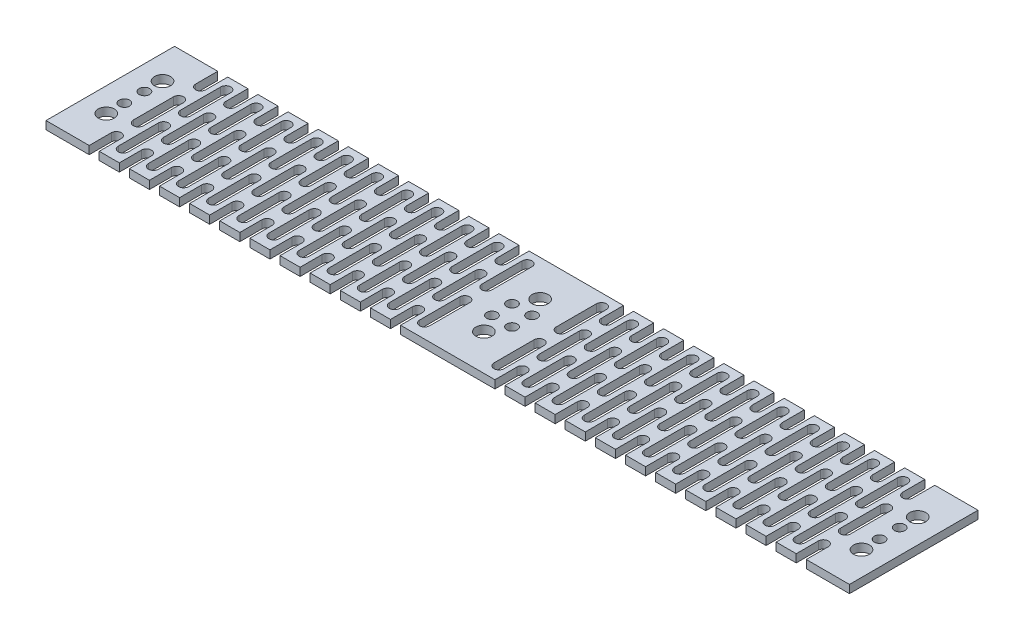
SolidWorks part; units mm, degrees
ref_plane "정면" through (0, 0, 0) normal (0, 0, 1) x (1, 0, 0)
ref_plane "윗면" through (0, 0, 0) normal (0, 1, 0) x (1, 0, 0)
ref_plane "우측면" through (0, 0, 0) normal (1, 0, 0) x (0, 0, -1)
sketch "스케치1" plane through (0, 0, 0) normal (0, 1, 0) x (1, 0, 0)
  line L1 (-50, 8) -> (50, 8)
  line L2 (-50, 8) -> (-50, -8)
  line L3 (-50, -8) -> (50, -8)
  line L4 (50, 8) -> (50, -8)
  dimension "D3" = 50
  dimension "D1" = 16
  dimension "D2" = 100
  dimension "D4" = 8
extrude "보스-돌출1" add sketch "스케치1" along normal blind 1 contours L1 L4 L3 L2
sketch "스케치2" plane through (0, 1, 0) normal (0, 1, 0) x (1, 0, 0)
  line L4 (50, 8) -> (50, -8) construction
  line L5 (-52.7608, 0) -> (58.8086, 0) construction
  line L6 (0, 14.085) -> (0, -13.5662) construction
  circle A2 centre (47, 3.5) radius 1
  circle A3 centre (0, 3.5) radius 1
  circle A4 centre (-47, 3.5) radius 1
  circle A8 centre (47, 1.25) radius 0.65
  circle A11 centre (-47, 1.25) radius 0.65
  circle A12 centre (47, -6.5) radius 1 [skipped]
  circle A13 centre (0, -6.5) radius 1 [skipped]
  circle A14 centre (-47, -6.5) radius 1 [skipped]
  circle A16 centre (1.25, 1.25) radius 0.65
  circle A17 centre (-1.25, 1.25) radius 0.65
  circle A18 centre (47, -1.25) radius 0.65
  circle A19 centre (47, -3.5) radius 1
  circle A20 centre (-1.25, -1.25) radius 0.65
  circle A21 centre (1.25, -1.25) radius 0.65
  circle A22 centre (0, -3.5) radius 1
  circle A23 centre (-47, -1.25) radius 0.65
  circle A24 centre (-47, -3.5) radius 1
  dimension "D4" = 2
  dimension "D9" = 1.3
  dimension "D11" = 2
  dimension "D5" = 3
  dimension "D6" = 3.5
  dimension "D10" = 1.25
  dimension "D12" = 2
  dimension "D7" = 3
  dimension "D8" = 2
extrude "컷-돌출1" cut sketch "스케치2" against normal through all
sketch "스케치3" plane through (0, 1, 0) normal (0, 1, 0) x (1, 0, 0)
  line L0 (44, 2.5) -> (44, -2.5) construction
  line L1 (44.625, 2.5) -> (44.625, -2.5)
  line L2 (43.375, 2.5) -> (43.375, -2.5)
  line L3 (-50, 8) -> (50, 8) construction
  line L4 (50, 8) -> (50, -8) construction
  line L5 (40.25, 2.5) -> (40.25, -2.5) construction
  line L6 (40.875, 2.5) -> (40.875, -2.5)
  line L7 (39.625, 2.5) -> (39.625, -2.5)
  line L8 (36.5, 2.5) -> (36.5, -2.5) construction
  line L9 (37.125, 2.5) -> (37.125, -2.5)
  line L10 (35.875, 2.5) -> (35.875, -2.5)
  line L11 (32.75, 2.5) -> (32.75, -2.5) construction
  line L12 (33.375, 2.5) -> (33.375, -2.5)
  line L13 (32.125, 2.5) -> (32.125, -2.5)
  line L14 (29, 2.5) -> (29, -2.5) construction
  line L15 (29.625, 2.5) -> (29.625, -2.5)
  line L16 (28.375, 2.5) -> (28.375, -2.5)
  line L17 (25.25, 2.5) -> (25.25, -2.5) construction
  line L18 (25.875, 2.5) -> (25.875, -2.5)
  line L19 (24.625, 2.5) -> (24.625, -2.5)
  line L20 (21.5, 2.5) -> (21.5, -2.5) construction
  line L21 (22.125, 2.5) -> (22.125, -2.5)
  line L22 (20.875, 2.5) -> (20.875, -2.5)
  line L23 (17.75, 2.5) -> (17.75, -2.5) construction
  line L24 (18.375, 2.5) -> (18.375, -2.5)
  line L25 (17.125, 2.5) -> (17.125, -2.5)
  line L26 (14, 2.5) -> (14, -2.5) construction
  line L27 (14.625, 2.5) -> (14.625, -2.5)
  line L28 (13.375, 2.5) -> (13.375, -2.5)
  line L29 (10.25, 2.5) -> (10.25, -2.5) construction
  line L30 (10.875, 2.5) -> (10.875, -2.5)
  line L31 (9.625, 2.5) -> (9.625, -2.5)
  line L32 (6.5, 2.5) -> (6.5, -2.5) construction
  line L33 (7.125, 2.5) -> (7.125, -2.5)
  line L34 (5.875, 2.5) -> (5.875, -2.5)
  line L35 (40.25, 10.25) -> (40.25, 5.25) construction
  line L36 (40.875, 10.25) -> (40.875, 5.25)
  line L37 (39.625, 10.25) -> (39.625, 5.25)
  line L38 (36.5, 10.25) -> (36.5, 5.25) construction
  line L39 (37.125, 10.25) -> (37.125, 5.25)
  line L40 (35.875, 10.25) -> (35.875, 5.25)
  line L41 (32.75, 10.25) -> (32.75, 5.25) construction
  line L42 (33.375, 10.25) -> (33.375, 5.25)
  line L43 (32.125, 10.25) -> (32.125, 5.25)
  line L44 (29, 10.25) -> (29, 5.25) construction
  line L45 (29.625, 10.25) -> (29.625, 5.25)
  line L46 (28.375, 10.25) -> (28.375, 5.25)
  line L47 (25.25, 10.25) -> (25.25, 5.25) construction
  line L48 (25.875, 10.25) -> (25.875, 5.25)
  line L49 (24.625, 10.25) -> (24.625, 5.25)
  line L50 (21.5, 10.25) -> (21.5, 5.25) construction
  line L51 (22.125, 10.25) -> (22.125, 5.25)
  line L52 (20.875, 10.25) -> (20.875, 5.25)
  line L53 (17.75, 10.25) -> (17.75, 5.25) construction
  line L54 (18.375, 10.25) -> (18.375, 5.25)
  line L55 (17.125, 10.25) -> (17.125, 5.25)
  line L56 (14, 10.25) -> (14, 5.25) construction
  line L57 (14.625, 10.25) -> (14.625, 5.25)
  line L58 (13.375, 10.25) -> (13.375, 5.25)
  line L59 (10.25, 10.25) -> (10.25, 5.25) construction
  line L60 (10.875, 10.25) -> (10.875, 5.25)
  line L61 (9.625, 10.25) -> (9.625, 5.25)
  line L62 (6.5, 10.25) -> (6.5, 5.25) construction
  line L63 (7.125, 10.25) -> (7.125, 5.25)
  line L64 (5.875, 10.25) -> (5.875, 5.25)
  line L65 (44, 10.25) -> (44, 5.25) construction
  line L66 (44.625, 10.25) -> (44.625, 5.25)
  line L67 (43.375, 10.25) -> (43.375, 5.25)
  line L68 (0, 0) -> (57.0875, 0) construction
  line L69 (-52.7608, 0) -> (58.8086, 0) construction
  line L70 (44, -10.25) -> (44, -5.25) construction
  line L71 (44.625, -10.25) -> (44.625, -5.25)
  line L72 (43.375, -10.25) -> (43.375, -5.25)
  line L73 (6.5, -10.25) -> (6.5, -5.25) construction
  line L74 (7.125, -10.25) -> (7.125, -5.25)
  line L75 (5.875, -10.25) -> (5.875, -5.25)
  line L76 (10.25, -10.25) -> (10.25, -5.25) construction
  line L77 (10.875, -10.25) -> (10.875, -5.25)
  line L78 (9.625, -10.25) -> (9.625, -5.25)
  line L79 (14, -10.25) -> (14, -5.25) construction
  line L80 (14.625, -10.25) -> (14.625, -5.25)
  line L81 (13.375, -10.25) -> (13.375, -5.25)
  line L82 (17.75, -10.25) -> (17.75, -5.25) construction
  line L83 (18.375, -10.25) -> (18.375, -5.25)
  line L84 (17.125, -10.25) -> (17.125, -5.25)
  line L85 (21.5, -10.25) -> (21.5, -5.25) construction
  line L86 (22.125, -10.25) -> (22.125, -5.25)
  line L87 (20.875, -10.25) -> (20.875, -5.25)
  line L88 (25.25, -10.25) -> (25.25, -5.25) construction
  line L89 (25.875, -10.25) -> (25.875, -5.25)
  line L90 (24.625, -10.25) -> (24.625, -5.25)
  line L91 (29, -10.25) -> (29, -5.25) construction
  line L92 (29.625, -10.25) -> (29.625, -5.25)
  line L93 (28.375, -10.25) -> (28.375, -5.25)
  line L94 (32.75, -10.25) -> (32.75, -5.25) construction
  line L95 (33.375, -10.25) -> (33.375, -5.25)
  line L96 (32.125, -10.25) -> (32.125, -5.25)
  line L97 (36.5, -10.25) -> (36.5, -5.25) construction
  line L98 (37.125, -10.25) -> (37.125, -5.25)
  line L99 (35.875, -10.25) -> (35.875, -5.25)
  line L100 (40.25, -10.25) -> (40.25, -5.25) construction
  line L101 (40.875, -10.25) -> (40.875, -5.25)
  line L102 (39.625, -10.25) -> (39.625, -5.25)
  line L103 (42.125, -1.25) -> (42.125, -6.25) construction
  line L104 (42.75, -1.25) -> (42.75, -6.25)
  line L105 (41.5, -1.25) -> (41.5, -6.25)
  line L106 (38.375, -1.25) -> (38.375, -6.25) construction
  line L107 (39, -1.25) -> (39, -6.25)
  line L108 (37.75, -1.25) -> (37.75, -6.25)
  line L109 (34.625, -1.25) -> (34.625, -6.25) construction
  line L110 (35.25, -1.25) -> (35.25, -6.25)
  line L111 (34, -1.25) -> (34, -6.25)
  line L112 (30.875, -1.25) -> (30.875, -6.25) construction
  line L113 (31.5, -1.25) -> (31.5, -6.25)
  line L114 (30.25, -1.25) -> (30.25, -6.25)
  line L115 (27.125, -1.25) -> (27.125, -6.25) construction
  line L116 (27.75, -1.25) -> (27.75, -6.25)
  line L117 (26.5, -1.25) -> (26.5, -6.25)
  line L118 (23.375, -1.25) -> (23.375, -6.25) construction
  line L119 (24, -1.25) -> (24, -6.25)
  line L120 (22.75, -1.25) -> (22.75, -6.25)
  line L121 (19.625, -1.25) -> (19.625, -6.25) construction
  line L122 (20.25, -1.25) -> (20.25, -6.25)
  line L123 (19, -1.25) -> (19, -6.25)
  line L124 (15.875, -1.25) -> (15.875, -6.25) construction
  line L125 (16.5, -1.25) -> (16.5, -6.25)
  line L126 (15.25, -1.25) -> (15.25, -6.25)
  line L127 (12.125, -1.25) -> (12.125, -6.25) construction
  line L128 (12.75, -1.25) -> (12.75, -6.25)
  line L129 (11.5, -1.25) -> (11.5, -6.25)
  line L130 (8.375, -1.25) -> (8.375, -6.25) construction
  line L131 (9, -1.25) -> (9, -6.25)
  line L132 (7.75, -1.25) -> (7.75, -6.25)
  line L133 (4.625, -1.25) -> (4.625, -6.25) construction
  line L134 (5.25, -1.25) -> (5.25, -6.25)
  line L135 (4, -1.25) -> (4, -6.25)
  line L136 (38.375, 6.5) -> (38.375, 1.5) construction
  line L137 (39, 6.5) -> (39, 1.5)
  line L138 (37.75, 6.5) -> (37.75, 1.5)
  line L139 (34.625, 6.5) -> (34.625, 1.5) construction
  line L140 (35.25, 6.5) -> (35.25, 1.5)
  line L141 (34, 6.5) -> (34, 1.5)
  line L142 (30.875, 6.5) -> (30.875, 1.5) construction
  line L143 (31.5, 6.5) -> (31.5, 1.5)
  line L144 (30.25, 6.5) -> (30.25, 1.5)
  line L145 (27.125, 6.5) -> (27.125, 1.5) construction
  line L146 (27.75, 6.5) -> (27.75, 1.5)
  line L147 (26.5, 6.5) -> (26.5, 1.5)
  line L148 (23.375, 6.5) -> (23.375, 1.5) construction
  line L149 (24, 6.5) -> (24, 1.5)
  line L150 (22.75, 6.5) -> (22.75, 1.5)
  line L151 (19.625, 6.5) -> (19.625, 1.5) construction
  line L152 (20.25, 6.5) -> (20.25, 1.5)
  line L153 (19, 6.5) -> (19, 1.5)
  line L154 (15.875, 6.5) -> (15.875, 1.5) construction
  line L155 (16.5, 6.5) -> (16.5, 1.5)
  line L156 (15.25, 6.5) -> (15.25, 1.5)
  line L157 (12.125, 6.5) -> (12.125, 1.5) construction
  line L158 (12.75, 6.5) -> (12.75, 1.5)
  line L159 (11.5, 6.5) -> (11.5, 1.5)
  line L160 (8.375, 6.5) -> (8.375, 1.5) construction
  line L161 (9, 6.5) -> (9, 1.5)
  line L162 (7.75, 6.5) -> (7.75, 1.5)
  line L163 (4.625, 6.5) -> (4.625, 1.5) construction
  line L164 (5.25, 6.5) -> (5.25, 1.5)
  line L165 (4, 6.5) -> (4, 1.5)
  line L166 (42.125, 6.5) -> (42.125, 1.5) construction
  line L167 (42.75, 6.5) -> (42.75, 1.5)
  line L168 (41.5, 6.5) -> (41.5, 1.5)
  line L169 (0, 14.085) -> (0, -13.5662) construction
  line L170 (-42.125, 6.5) -> (-42.125, 1.5) construction
  line L171 (-42.75, 6.5) -> (-42.75, 1.5)
  line L172 (-41.5, 6.5) -> (-41.5, 1.5)
  line L173 (-4.625, 6.5) -> (-4.625, 1.5) construction
  line L174 (-5.25, 6.5) -> (-5.25, 1.5)
  line L175 (-4, 6.5) -> (-4, 1.5)
  line L176 (-8.375, 6.5) -> (-8.375, 1.5) construction
  line L177 (-9, 6.5) -> (-9, 1.5)
  line L178 (-7.75, 6.5) -> (-7.75, 1.5)
  line L179 (-12.125, 6.5) -> (-12.125, 1.5) construction
  line L180 (-12.75, 6.5) -> (-12.75, 1.5)
  line L181 (-11.5, 6.5) -> (-11.5, 1.5)
  line L182 (-15.875, 6.5) -> (-15.875, 1.5) construction
  line L183 (-16.5, 6.5) -> (-16.5, 1.5)
  line L184 (-15.25, 6.5) -> (-15.25, 1.5)
  line L185 (-19.625, 6.5) -> (-19.625, 1.5) construction
  line L186 (-20.25, 6.5) -> (-20.25, 1.5)
  line L187 (-19, 6.5) -> (-19, 1.5)
  line L188 (-23.375, 6.5) -> (-23.375, 1.5) construction
  line L189 (-24, 6.5) -> (-24, 1.5)
  line L190 (-22.75, 6.5) -> (-22.75, 1.5)
  line L191 (-27.125, 6.5) -> (-27.125, 1.5) construction
  line L192 (-27.75, 6.5) -> (-27.75, 1.5)
  line L193 (-26.5, 6.5) -> (-26.5, 1.5)
  line L194 (-30.875, 6.5) -> (-30.875, 1.5) construction
  line L195 (-31.5, 6.5) -> (-31.5, 1.5)
  line L196 (-30.25, 6.5) -> (-30.25, 1.5)
  line L197 (-34.625, 6.5) -> (-34.625, 1.5) construction
  line L198 (-35.25, 6.5) -> (-35.25, 1.5)
  line L199 (-34, 6.5) -> (-34, 1.5)
  line L200 (-38.375, 6.5) -> (-38.375, 1.5) construction
  line L201 (-39, 6.5) -> (-39, 1.5)
  line L202 (-37.75, 6.5) -> (-37.75, 1.5)
  line L203 (-4.625, -1.25) -> (-4.625, -6.25) construction
  line L204 (-5.25, -1.25) -> (-5.25, -6.25)
  line L205 (-4, -1.25) -> (-4, -6.25)
  line L206 (-8.375, -1.25) -> (-8.375, -6.25) construction
  line L207 (-9, -1.25) -> (-9, -6.25)
  line L208 (-7.75, -1.25) -> (-7.75, -6.25)
  line L209 (-12.125, -1.25) -> (-12.125, -6.25) construction
  line L210 (-12.75, -1.25) -> (-12.75, -6.25)
  line L211 (-11.5, -1.25) -> (-11.5, -6.25)
  line L212 (-15.875, -1.25) -> (-15.875, -6.25) construction
  line L213 (-16.5, -1.25) -> (-16.5, -6.25)
  line L214 (-15.25, -1.25) -> (-15.25, -6.25)
  line L215 (-19.625, -1.25) -> (-19.625, -6.25) construction
  line L216 (-20.25, -1.25) -> (-20.25, -6.25)
  line L217 (-19, -1.25) -> (-19, -6.25)
  line L218 (-23.375, -1.25) -> (-23.375, -6.25) construction
  line L219 (-24, -1.25) -> (-24, -6.25)
  line L220 (-22.75, -1.25) -> (-22.75, -6.25)
  line L221 (-27.125, -1.25) -> (-27.125, -6.25) construction
  line L222 (-27.75, -1.25) -> (-27.75, -6.25)
  line L223 (-26.5, -1.25) -> (-26.5, -6.25)
  line L224 (-30.875, -1.25) -> (-30.875, -6.25) construction
  line L225 (-31.5, -1.25) -> (-31.5, -6.25)
  line L226 (-30.25, -1.25) -> (-30.25, -6.25)
  line L227 (-34.625, -1.25) -> (-34.625, -6.25) construction
  line L228 (-35.25, -1.25) -> (-35.25, -6.25)
  line L229 (-34, -1.25) -> (-34, -6.25)
  line L230 (-38.375, -1.25) -> (-38.375, -6.25) construction
  line L231 (-39, -1.25) -> (-39, -6.25)
  line L232 (-37.75, -1.25) -> (-37.75, -6.25)
  line L233 (-42.125, -1.25) -> (-42.125, -6.25) construction
  line L234 (-42.75, -1.25) -> (-42.75, -6.25)
  line L235 (-41.5, -1.25) -> (-41.5, -6.25)
  line L236 (-40.25, -10.25) -> (-40.25, -5.25) construction
  line L237 (-40.875, -10.25) -> (-40.875, -5.25)
  line L238 (-39.625, -10.25) -> (-39.625, -5.25)
  line L239 (-36.5, -10.25) -> (-36.5, -5.25) construction
  line L240 (-37.125, -10.25) -> (-37.125, -5.25)
  line L241 (-35.875, -10.25) -> (-35.875, -5.25)
  line L242 (-32.75, -10.25) -> (-32.75, -5.25) construction
  line L243 (-33.375, -10.25) -> (-33.375, -5.25)
  line L244 (-32.125, -10.25) -> (-32.125, -5.25)
  line L245 (-29, -10.25) -> (-29, -5.25) construction
  line L246 (-29.625, -10.25) -> (-29.625, -5.25)
  line L247 (-28.375, -10.25) -> (-28.375, -5.25)
  line L248 (-25.25, -10.25) -> (-25.25, -5.25) construction
  line L249 (-25.875, -10.25) -> (-25.875, -5.25)
  line L250 (-24.625, -10.25) -> (-24.625, -5.25)
  line L251 (-21.5, -10.25) -> (-21.5, -5.25) construction
  line L252 (-22.125, -10.25) -> (-22.125, -5.25)
  line L253 (-20.875, -10.25) -> (-20.875, -5.25)
  line L254 (-17.75, -10.25) -> (-17.75, -5.25) construction
  line L255 (-18.375, -10.25) -> (-18.375, -5.25)
  line L256 (-17.125, -10.25) -> (-17.125, -5.25)
  line L257 (-14, -10.25) -> (-14, -5.25) construction
  line L258 (-14.625, -10.25) -> (-14.625, -5.25)
  line L259 (-13.375, -10.25) -> (-13.375, -5.25)
  line L260 (-10.25, -10.25) -> (-10.25, -5.25) construction
  line L261 (-10.875, -10.25) -> (-10.875, -5.25)
  line L262 (-9.625, -10.25) -> (-9.625, -5.25)
  line L263 (-6.5, -10.25) -> (-6.5, -5.25) construction
  line L264 (-7.125, -10.25) -> (-7.125, -5.25)
  line L265 (-5.875, -10.25) -> (-5.875, -5.25)
  line L266 (-44, -10.25) -> (-44, -5.25) construction
  line L267 (-44.625, -10.25) -> (-44.625, -5.25)
  line L268 (-43.375, -10.25) -> (-43.375, -5.25)
  line L269 (-44, 10.25) -> (-44, 5.25) construction
  line L270 (-44.625, 10.25) -> (-44.625, 5.25)
  line L271 (-43.375, 10.25) -> (-43.375, 5.25)
  line L272 (-6.5, 10.25) -> (-6.5, 5.25) construction
  line L273 (-7.125, 10.25) -> (-7.125, 5.25)
  line L274 (-5.875, 10.25) -> (-5.875, 5.25)
  line L275 (-10.25, 10.25) -> (-10.25, 5.25) construction
  line L276 (-10.875, 10.25) -> (-10.875, 5.25)
  line L277 (-9.625, 10.25) -> (-9.625, 5.25)
  line L278 (-14, 10.25) -> (-14, 5.25) construction
  line L279 (-14.625, 10.25) -> (-14.625, 5.25)
  line L280 (-13.375, 10.25) -> (-13.375, 5.25)
  line L281 (-17.75, 10.25) -> (-17.75, 5.25) construction
  line L282 (-18.375, 10.25) -> (-18.375, 5.25)
  line L283 (-17.125, 10.25) -> (-17.125, 5.25)
  line L284 (-21.5, 10.25) -> (-21.5, 5.25) construction
  line L285 (-22.125, 10.25) -> (-22.125, 5.25)
  line L286 (-20.875, 10.25) -> (-20.875, 5.25)
  line L287 (-25.25, 10.25) -> (-25.25, 5.25) construction
  line L288 (-25.875, 10.25) -> (-25.875, 5.25)
  line L289 (-24.625, 10.25) -> (-24.625, 5.25)
  line L290 (-29, 10.25) -> (-29, 5.25) construction
  line L291 (-29.625, 10.25) -> (-29.625, 5.25)
  line L292 (-28.375, 10.25) -> (-28.375, 5.25)
  line L293 (-32.75, 10.25) -> (-32.75, 5.25) construction
  line L294 (-33.375, 10.25) -> (-33.375, 5.25)
  line L295 (-32.125, 10.25) -> (-32.125, 5.25)
  line L296 (-36.5, 10.25) -> (-36.5, 5.25) construction
  line L297 (-37.125, 10.25) -> (-37.125, 5.25)
  line L298 (-35.875, 10.25) -> (-35.875, 5.25)
  line L299 (-40.25, 10.25) -> (-40.25, 5.25) construction
  line L300 (-40.875, 10.25) -> (-40.875, 5.25)
  line L301 (-39.625, 10.25) -> (-39.625, 5.25)
  line L302 (-6.5, 2.5) -> (-6.5, -2.5) construction
  line L303 (-7.125, 2.5) -> (-7.125, -2.5)
  line L304 (-5.875, 2.5) -> (-5.875, -2.5)
  line L305 (-10.25, 2.5) -> (-10.25, -2.5) construction
  line L306 (-10.875, 2.5) -> (-10.875, -2.5)
  line L307 (-9.625, 2.5) -> (-9.625, -2.5)
  line L308 (-14, 2.5) -> (-14, -2.5) construction
  line L309 (-14.625, 2.5) -> (-14.625, -2.5)
  line L310 (-13.375, 2.5) -> (-13.375, -2.5)
  line L311 (-17.75, 2.5) -> (-17.75, -2.5) construction
  line L312 (-18.375, 2.5) -> (-18.375, -2.5)
  line L313 (-17.125, 2.5) -> (-17.125, -2.5)
  line L314 (-21.5, 2.5) -> (-21.5, -2.5) construction
  line L315 (-22.125, 2.5) -> (-22.125, -2.5)
  line L316 (-20.875, 2.5) -> (-20.875, -2.5)
  line L317 (-25.25, 2.5) -> (-25.25, -2.5) construction
  line L318 (-25.875, 2.5) -> (-25.875, -2.5)
  line L319 (-24.625, 2.5) -> (-24.625, -2.5)
  line L320 (-29, 2.5) -> (-29, -2.5) construction
  line L321 (-29.625, 2.5) -> (-29.625, -2.5)
  line L322 (-28.375, 2.5) -> (-28.375, -2.5)
  line L323 (-32.75, 2.5) -> (-32.75, -2.5) construction
  line L324 (-33.375, 2.5) -> (-33.375, -2.5)
  line L325 (-32.125, 2.5) -> (-32.125, -2.5)
  line L326 (-36.5, 2.5) -> (-36.5, -2.5) construction
  line L327 (-37.125, 2.5) -> (-37.125, -2.5)
  line L328 (-35.875, 2.5) -> (-35.875, -2.5)
  line L329 (-40.25, 2.5) -> (-40.25, -2.5) construction
  line L330 (-40.875, 2.5) -> (-40.875, -2.5)
  line L331 (-39.625, 2.5) -> (-39.625, -2.5)
  line L332 (-44, 2.5) -> (-44, -2.5) construction
  line L333 (-44.625, 2.5) -> (-44.625, -2.5)
  line L334 (-43.375, 2.5) -> (-43.375, -2.5)
  arc A0 (44.625, 2.5) -> (43.375, 2.5) centre (44, 2.5) ccw
  arc A1 (43.375, -2.5) -> (44.625, -2.5) centre (44, -2.5) ccw
  arc A2 (40.875, 2.5) -> (39.625, 2.5) centre (40.25, 2.5) ccw
  arc A3 (39.625, -2.5) -> (40.875, -2.5) centre (40.25, -2.5) ccw
  arc A4 (37.125, 2.5) -> (35.875, 2.5) centre (36.5, 2.5) ccw
  arc A5 (35.875, -2.5) -> (37.125, -2.5) centre (36.5, -2.5) ccw
  arc A6 (33.375, 2.5) -> (32.125, 2.5) centre (32.75, 2.5) ccw
  arc A7 (32.125, -2.5) -> (33.375, -2.5) centre (32.75, -2.5) ccw
  arc A8 (29.625, 2.5) -> (28.375, 2.5) centre (29, 2.5) ccw
  arc A9 (28.375, -2.5) -> (29.625, -2.5) centre (29, -2.5) ccw
  arc A10 (25.875, 2.5) -> (24.625, 2.5) centre (25.25, 2.5) ccw
  arc A11 (24.625, -2.5) -> (25.875, -2.5) centre (25.25, -2.5) ccw
  arc A12 (22.125, 2.5) -> (20.875, 2.5) centre (21.5, 2.5) ccw
  arc A13 (20.875, -2.5) -> (22.125, -2.5) centre (21.5, -2.5) ccw
  arc A14 (18.375, 2.5) -> (17.125, 2.5) centre (17.75, 2.5) ccw
  arc A15 (17.125, -2.5) -> (18.375, -2.5) centre (17.75, -2.5) ccw
  arc A16 (14.625, 2.5) -> (13.375, 2.5) centre (14, 2.5) ccw
  arc A17 (13.375, -2.5) -> (14.625, -2.5) centre (14, -2.5) ccw
  arc A18 (10.875, 2.5) -> (9.625, 2.5) centre (10.25, 2.5) ccw
  arc A19 (9.625, -2.5) -> (10.875, -2.5) centre (10.25, -2.5) ccw
  arc A20 (7.125, 2.5) -> (5.875, 2.5) centre (6.5, 2.5) ccw
  arc A21 (5.875, -2.5) -> (7.125, -2.5) centre (6.5, -2.5) ccw
  arc A22 (40.875, 10.25) -> (39.625, 10.25) centre (40.25, 10.25) ccw
  arc A23 (39.625, 5.25) -> (40.875, 5.25) centre (40.25, 5.25) ccw
  arc A24 (37.125, 10.25) -> (35.875, 10.25) centre (36.5, 10.25) ccw
  arc A25 (35.875, 5.25) -> (37.125, 5.25) centre (36.5, 5.25) ccw
  arc A26 (33.375, 10.25) -> (32.125, 10.25) centre (32.75, 10.25) ccw
  arc A27 (32.125, 5.25) -> (33.375, 5.25) centre (32.75, 5.25) ccw
  arc A28 (29.625, 10.25) -> (28.375, 10.25) centre (29, 10.25) ccw
  arc A29 (28.375, 5.25) -> (29.625, 5.25) centre (29, 5.25) ccw
  arc A30 (25.875, 10.25) -> (24.625, 10.25) centre (25.25, 10.25) ccw
  arc A31 (24.625, 5.25) -> (25.875, 5.25) centre (25.25, 5.25) ccw
  arc A32 (22.125, 10.25) -> (20.875, 10.25) centre (21.5, 10.25) ccw
  arc A33 (20.875, 5.25) -> (22.125, 5.25) centre (21.5, 5.25) ccw
  arc A34 (18.375, 10.25) -> (17.125, 10.25) centre (17.75, 10.25) ccw
  arc A35 (17.125, 5.25) -> (18.375, 5.25) centre (17.75, 5.25) ccw
  arc A36 (14.625, 10.25) -> (13.375, 10.25) centre (14, 10.25) ccw
  arc A37 (13.375, 5.25) -> (14.625, 5.25) centre (14, 5.25) ccw
  arc A38 (10.875, 10.25) -> (9.625, 10.25) centre (10.25, 10.25) ccw
  arc A39 (9.625, 5.25) -> (10.875, 5.25) centre (10.25, 5.25) ccw
  arc A40 (7.125, 10.25) -> (5.875, 10.25) centre (6.5, 10.25) ccw
  arc A41 (5.875, 5.25) -> (7.125, 5.25) centre (6.5, 5.25) ccw
  arc A42 (44.625, 10.25) -> (43.375, 10.25) centre (44, 10.25) ccw
  arc A43 (43.375, 5.25) -> (44.625, 5.25) centre (44, 5.25) ccw
  arc A44 (44.625, -10.25) -> (43.375, -10.25) centre (44, -10.25) cw
  arc A45 (43.375, -5.25) -> (44.625, -5.25) centre (44, -5.25) cw
  arc A46 (7.125, -10.25) -> (5.875, -10.25) centre (6.5, -10.25) cw
  arc A47 (5.875, -5.25) -> (7.125, -5.25) centre (6.5, -5.25) cw
  arc A48 (10.875, -10.25) -> (9.625, -10.25) centre (10.25, -10.25) cw
  arc A49 (9.625, -5.25) -> (10.875, -5.25) centre (10.25, -5.25) cw
  arc A50 (14.625, -10.25) -> (13.375, -10.25) centre (14, -10.25) cw
  arc A51 (13.375, -5.25) -> (14.625, -5.25) centre (14, -5.25) cw
  arc A52 (18.375, -10.25) -> (17.125, -10.25) centre (17.75, -10.25) cw
  arc A53 (17.125, -5.25) -> (18.375, -5.25) centre (17.75, -5.25) cw
  arc A54 (22.125, -10.25) -> (20.875, -10.25) centre (21.5, -10.25) cw
  arc A55 (20.875, -5.25) -> (22.125, -5.25) centre (21.5, -5.25) cw
  arc A56 (25.875, -10.25) -> (24.625, -10.25) centre (25.25, -10.25) cw
  arc A57 (24.625, -5.25) -> (25.875, -5.25) centre (25.25, -5.25) cw
  arc A58 (29.625, -10.25) -> (28.375, -10.25) centre (29, -10.25) cw
  arc A59 (28.375, -5.25) -> (29.625, -5.25) centre (29, -5.25) cw
  arc A60 (33.375, -10.25) -> (32.125, -10.25) centre (32.75, -10.25) cw
  arc A61 (32.125, -5.25) -> (33.375, -5.25) centre (32.75, -5.25) cw
  arc A62 (37.125, -10.25) -> (35.875, -10.25) centre (36.5, -10.25) cw
  arc A63 (35.875, -5.25) -> (37.125, -5.25) centre (36.5, -5.25) cw
  arc A64 (40.875, -10.25) -> (39.625, -10.25) centre (40.25, -10.25) cw
  arc A65 (39.625, -5.25) -> (40.875, -5.25) centre (40.25, -5.25) cw
  arc A66 (42.75, -1.25) -> (41.5, -1.25) centre (42.125, -1.25) ccw
  arc A67 (41.5, -6.25) -> (42.75, -6.25) centre (42.125, -6.25) ccw
  arc A68 (39, -1.25) -> (37.75, -1.25) centre (38.375, -1.25) ccw
  arc A69 (37.75, -6.25) -> (39, -6.25) centre (38.375, -6.25) ccw
  arc A70 (35.25, -1.25) -> (34, -1.25) centre (34.625, -1.25) ccw
  arc A71 (34, -6.25) -> (35.25, -6.25) centre (34.625, -6.25) ccw
  arc A72 (31.5, -1.25) -> (30.25, -1.25) centre (30.875, -1.25) ccw
  arc A73 (30.25, -6.25) -> (31.5, -6.25) centre (30.875, -6.25) ccw
  arc A74 (27.75, -1.25) -> (26.5, -1.25) centre (27.125, -1.25) ccw
  arc A75 (26.5, -6.25) -> (27.75, -6.25) centre (27.125, -6.25) ccw
  arc A76 (24, -1.25) -> (22.75, -1.25) centre (23.375, -1.25) ccw
  arc A77 (22.75, -6.25) -> (24, -6.25) centre (23.375, -6.25) ccw
  arc A78 (20.25, -1.25) -> (19, -1.25) centre (19.625, -1.25) ccw
  arc A79 (19, -6.25) -> (20.25, -6.25) centre (19.625, -6.25) ccw
  arc A80 (16.5, -1.25) -> (15.25, -1.25) centre (15.875, -1.25) ccw
  arc A81 (15.25, -6.25) -> (16.5, -6.25) centre (15.875, -6.25) ccw
  arc A82 (12.75, -1.25) -> (11.5, -1.25) centre (12.125, -1.25) ccw
  arc A83 (11.5, -6.25) -> (12.75, -6.25) centre (12.125, -6.25) ccw
  arc A84 (9, -1.25) -> (7.75, -1.25) centre (8.375, -1.25) ccw
  arc A85 (7.75, -6.25) -> (9, -6.25) centre (8.375, -6.25) ccw
  arc A86 (5.25, -1.25) -> (4, -1.25) centre (4.625, -1.25) ccw
  arc A87 (4, -6.25) -> (5.25, -6.25) centre (4.625, -6.25) ccw
  arc A88 (39, 6.5) -> (37.75, 6.5) centre (38.375, 6.5) ccw
  arc A89 (37.75, 1.5) -> (39, 1.5) centre (38.375, 1.5) ccw
  arc A90 (35.25, 6.5) -> (34, 6.5) centre (34.625, 6.5) ccw
  arc A91 (34, 1.5) -> (35.25, 1.5) centre (34.625, 1.5) ccw
  arc A92 (31.5, 6.5) -> (30.25, 6.5) centre (30.875, 6.5) ccw
  arc A93 (30.25, 1.5) -> (31.5, 1.5) centre (30.875, 1.5) ccw
  arc A94 (27.75, 6.5) -> (26.5, 6.5) centre (27.125, 6.5) ccw
  arc A95 (26.5, 1.5) -> (27.75, 1.5) centre (27.125, 1.5) ccw
  arc A96 (24, 6.5) -> (22.75, 6.5) centre (23.375, 6.5) ccw
  arc A97 (22.75, 1.5) -> (24, 1.5) centre (23.375, 1.5) ccw
  arc A98 (20.25, 6.5) -> (19, 6.5) centre (19.625, 6.5) ccw
  arc A99 (19, 1.5) -> (20.25, 1.5) centre (19.625, 1.5) ccw
  arc A100 (16.5, 6.5) -> (15.25, 6.5) centre (15.875, 6.5) ccw
  arc A101 (15.25, 1.5) -> (16.5, 1.5) centre (15.875, 1.5) ccw
  arc A102 (12.75, 6.5) -> (11.5, 6.5) centre (12.125, 6.5) ccw
  arc A103 (11.5, 1.5) -> (12.75, 1.5) centre (12.125, 1.5) ccw
  arc A104 (9, 6.5) -> (7.75, 6.5) centre (8.375, 6.5) ccw
  arc A105 (7.75, 1.5) -> (9, 1.5) centre (8.375, 1.5) ccw
  arc A106 (5.25, 6.5) -> (4, 6.5) centre (4.625, 6.5) ccw
  arc A107 (4, 1.5) -> (5.25, 1.5) centre (4.625, 1.5) ccw
  arc A108 (42.75, 6.5) -> (41.5, 6.5) centre (42.125, 6.5) ccw
  arc A109 (41.5, 1.5) -> (42.75, 1.5) centre (42.125, 1.5) ccw
  arc A110 (-42.75, 6.5) -> (-41.5, 6.5) centre (-42.125, 6.5) cw
  arc A111 (-41.5, 1.5) -> (-42.75, 1.5) centre (-42.125, 1.5) cw
  arc A112 (-5.25, 6.5) -> (-4, 6.5) centre (-4.625, 6.5) cw
  arc A113 (-4, 1.5) -> (-5.25, 1.5) centre (-4.625, 1.5) cw
  arc A114 (-9, 6.5) -> (-7.75, 6.5) centre (-8.375, 6.5) cw
  arc A115 (-7.75, 1.5) -> (-9, 1.5) centre (-8.375, 1.5) cw
  arc A116 (-12.75, 6.5) -> (-11.5, 6.5) centre (-12.125, 6.5) cw
  arc A117 (-11.5, 1.5) -> (-12.75, 1.5) centre (-12.125, 1.5) cw
  arc A118 (-16.5, 6.5) -> (-15.25, 6.5) centre (-15.875, 6.5) cw
  arc A119 (-15.25, 1.5) -> (-16.5, 1.5) centre (-15.875, 1.5) cw
  arc A120 (-20.25, 6.5) -> (-19, 6.5) centre (-19.625, 6.5) cw
  arc A121 (-19, 1.5) -> (-20.25, 1.5) centre (-19.625, 1.5) cw
  arc A122 (-24, 6.5) -> (-22.75, 6.5) centre (-23.375, 6.5) cw
  arc A123 (-22.75, 1.5) -> (-24, 1.5) centre (-23.375, 1.5) cw
  arc A124 (-27.75, 6.5) -> (-26.5, 6.5) centre (-27.125, 6.5) cw
  arc A125 (-26.5, 1.5) -> (-27.75, 1.5) centre (-27.125, 1.5) cw
  arc A126 (-31.5, 6.5) -> (-30.25, 6.5) centre (-30.875, 6.5) cw
  arc A127 (-30.25, 1.5) -> (-31.5, 1.5) centre (-30.875, 1.5) cw
  arc A128 (-35.25, 6.5) -> (-34, 6.5) centre (-34.625, 6.5) cw
  arc A129 (-34, 1.5) -> (-35.25, 1.5) centre (-34.625, 1.5) cw
  arc A130 (-39, 6.5) -> (-37.75, 6.5) centre (-38.375, 6.5) cw
  arc A131 (-37.75, 1.5) -> (-39, 1.5) centre (-38.375, 1.5) cw
  arc A132 (-5.25, -1.25) -> (-4, -1.25) centre (-4.625, -1.25) cw
  arc A133 (-4, -6.25) -> (-5.25, -6.25) centre (-4.625, -6.25) cw
  arc A134 (-9, -1.25) -> (-7.75, -1.25) centre (-8.375, -1.25) cw
  arc A135 (-7.75, -6.25) -> (-9, -6.25) centre (-8.375, -6.25) cw
  arc A136 (-12.75, -1.25) -> (-11.5, -1.25) centre (-12.125, -1.25) cw
  arc A137 (-11.5, -6.25) -> (-12.75, -6.25) centre (-12.125, -6.25) cw
  arc A138 (-16.5, -1.25) -> (-15.25, -1.25) centre (-15.875, -1.25) cw
  arc A139 (-15.25, -6.25) -> (-16.5, -6.25) centre (-15.875, -6.25) cw
  arc A140 (-20.25, -1.25) -> (-19, -1.25) centre (-19.625, -1.25) cw
  arc A141 (-19, -6.25) -> (-20.25, -6.25) centre (-19.625, -6.25) cw
  arc A142 (-24, -1.25) -> (-22.75, -1.25) centre (-23.375, -1.25) cw
  arc A143 (-22.75, -6.25) -> (-24, -6.25) centre (-23.375, -6.25) cw
  arc A144 (-27.75, -1.25) -> (-26.5, -1.25) centre (-27.125, -1.25) cw
  arc A145 (-26.5, -6.25) -> (-27.75, -6.25) centre (-27.125, -6.25) cw
  arc A146 (-31.5, -1.25) -> (-30.25, -1.25) centre (-30.875, -1.25) cw
  arc A147 (-30.25, -6.25) -> (-31.5, -6.25) centre (-30.875, -6.25) cw
  arc A148 (-35.25, -1.25) -> (-34, -1.25) centre (-34.625, -1.25) cw
  arc A149 (-34, -6.25) -> (-35.25, -6.25) centre (-34.625, -6.25) cw
  arc A150 (-39, -1.25) -> (-37.75, -1.25) centre (-38.375, -1.25) cw
  arc A151 (-37.75, -6.25) -> (-39, -6.25) centre (-38.375, -6.25) cw
  arc A152 (-42.75, -1.25) -> (-41.5, -1.25) centre (-42.125, -1.25) cw
  arc A153 (-41.5, -6.25) -> (-42.75, -6.25) centre (-42.125, -6.25) cw
  arc A154 (-40.875, -10.25) -> (-39.625, -10.25) centre (-40.25, -10.25) ccw
  arc A155 (-39.625, -5.25) -> (-40.875, -5.25) centre (-40.25, -5.25) ccw
  arc A156 (-37.125, -10.25) -> (-35.875, -10.25) centre (-36.5, -10.25) ccw
  arc A157 (-35.875, -5.25) -> (-37.125, -5.25) centre (-36.5, -5.25) ccw
  arc A158 (-33.375, -10.25) -> (-32.125, -10.25) centre (-32.75, -10.25) ccw
  arc A159 (-32.125, -5.25) -> (-33.375, -5.25) centre (-32.75, -5.25) ccw
  arc A160 (-29.625, -10.25) -> (-28.375, -10.25) centre (-29, -10.25) ccw
  arc A161 (-28.375, -5.25) -> (-29.625, -5.25) centre (-29, -5.25) ccw
  arc A162 (-25.875, -10.25) -> (-24.625, -10.25) centre (-25.25, -10.25) ccw
  arc A163 (-24.625, -5.25) -> (-25.875, -5.25) centre (-25.25, -5.25) ccw
  arc A164 (-22.125, -10.25) -> (-20.875, -10.25) centre (-21.5, -10.25) ccw
  arc A165 (-20.875, -5.25) -> (-22.125, -5.25) centre (-21.5, -5.25) ccw
  arc A166 (-18.375, -10.25) -> (-17.125, -10.25) centre (-17.75, -10.25) ccw
  arc A167 (-17.125, -5.25) -> (-18.375, -5.25) centre (-17.75, -5.25) ccw
  arc A168 (-14.625, -10.25) -> (-13.375, -10.25) centre (-14, -10.25) ccw
  arc A169 (-13.375, -5.25) -> (-14.625, -5.25) centre (-14, -5.25) ccw
  arc A170 (-10.875, -10.25) -> (-9.625, -10.25) centre (-10.25, -10.25) ccw
  arc A171 (-9.625, -5.25) -> (-10.875, -5.25) centre (-10.25, -5.25) ccw
  arc A172 (-7.125, -10.25) -> (-5.875, -10.25) centre (-6.5, -10.25) ccw
  arc A173 (-5.875, -5.25) -> (-7.125, -5.25) centre (-6.5, -5.25) ccw
  arc A174 (-44.625, -10.25) -> (-43.375, -10.25) centre (-44, -10.25) ccw
  arc A175 (-43.375, -5.25) -> (-44.625, -5.25) centre (-44, -5.25) ccw
  arc A176 (-44.625, 10.25) -> (-43.375, 10.25) centre (-44, 10.25) cw
  arc A177 (-43.375, 5.25) -> (-44.625, 5.25) centre (-44, 5.25) cw
  arc A178 (-7.125, 10.25) -> (-5.875, 10.25) centre (-6.5, 10.25) cw
  arc A179 (-5.875, 5.25) -> (-7.125, 5.25) centre (-6.5, 5.25) cw
  arc A180 (-10.875, 10.25) -> (-9.625, 10.25) centre (-10.25, 10.25) cw
  arc A181 (-9.625, 5.25) -> (-10.875, 5.25) centre (-10.25, 5.25) cw
  arc A182 (-14.625, 10.25) -> (-13.375, 10.25) centre (-14, 10.25) cw
  arc A183 (-13.375, 5.25) -> (-14.625, 5.25) centre (-14, 5.25) cw
  arc A184 (-18.375, 10.25) -> (-17.125, 10.25) centre (-17.75, 10.25) cw
  arc A185 (-17.125, 5.25) -> (-18.375, 5.25) centre (-17.75, 5.25) cw
  arc A186 (-22.125, 10.25) -> (-20.875, 10.25) centre (-21.5, 10.25) cw
  arc A187 (-20.875, 5.25) -> (-22.125, 5.25) centre (-21.5, 5.25) cw
  arc A188 (-25.875, 10.25) -> (-24.625, 10.25) centre (-25.25, 10.25) cw
  arc A189 (-24.625, 5.25) -> (-25.875, 5.25) centre (-25.25, 5.25) cw
  arc A190 (-29.625, 10.25) -> (-28.375, 10.25) centre (-29, 10.25) cw
  arc A191 (-28.375, 5.25) -> (-29.625, 5.25) centre (-29, 5.25) cw
  arc A192 (-33.375, 10.25) -> (-32.125, 10.25) centre (-32.75, 10.25) cw
  arc A193 (-32.125, 5.25) -> (-33.375, 5.25) centre (-32.75, 5.25) cw
  arc A194 (-37.125, 10.25) -> (-35.875, 10.25) centre (-36.5, 10.25) cw
  arc A195 (-35.875, 5.25) -> (-37.125, 5.25) centre (-36.5, 5.25) cw
  arc A196 (-40.875, 10.25) -> (-39.625, 10.25) centre (-40.25, 10.25) cw
  arc A197 (-39.625, 5.25) -> (-40.875, 5.25) centre (-40.25, 5.25) cw
  arc A198 (-7.125, 2.5) -> (-5.875, 2.5) centre (-6.5, 2.5) cw
  arc A199 (-5.875, -2.5) -> (-7.125, -2.5) centre (-6.5, -2.5) cw
  arc A200 (-10.875, 2.5) -> (-9.625, 2.5) centre (-10.25, 2.5) cw
  arc A201 (-9.625, -2.5) -> (-10.875, -2.5) centre (-10.25, -2.5) cw
  arc A202 (-14.625, 2.5) -> (-13.375, 2.5) centre (-14, 2.5) cw
  arc A203 (-13.375, -2.5) -> (-14.625, -2.5) centre (-14, -2.5) cw
  arc A204 (-18.375, 2.5) -> (-17.125, 2.5) centre (-17.75, 2.5) cw
  arc A205 (-17.125, -2.5) -> (-18.375, -2.5) centre (-17.75, -2.5) cw
  arc A206 (-22.125, 2.5) -> (-20.875, 2.5) centre (-21.5, 2.5) cw
  arc A207 (-20.875, -2.5) -> (-22.125, -2.5) centre (-21.5, -2.5) cw
  arc A208 (-25.875, 2.5) -> (-24.625, 2.5) centre (-25.25, 2.5) cw
  arc A209 (-24.625, -2.5) -> (-25.875, -2.5) centre (-25.25, -2.5) cw
  arc A210 (-29.625, 2.5) -> (-28.375, 2.5) centre (-29, 2.5) cw
  arc A211 (-28.375, -2.5) -> (-29.625, -2.5) centre (-29, -2.5) cw
  arc A212 (-33.375, 2.5) -> (-32.125, 2.5) centre (-32.75, 2.5) cw
  arc A213 (-32.125, -2.5) -> (-33.375, -2.5) centre (-32.75, -2.5) cw
  arc A214 (-37.125, 2.5) -> (-35.875, 2.5) centre (-36.5, 2.5) cw
  arc A215 (-35.875, -2.5) -> (-37.125, -2.5) centre (-36.5, -2.5) cw
  arc A216 (-40.875, 2.5) -> (-39.625, 2.5) centre (-40.25, 2.5) cw
  arc A217 (-39.625, -2.5) -> (-40.875, -2.5) centre (-40.25, -2.5) cw
  arc A218 (-44.625, 2.5) -> (-43.375, 2.5) centre (-44, 2.5) cw
  arc A219 (-43.375, -2.5) -> (-44.625, -2.5) centre (-44, -2.5) cw
  point P2 (44, 0)
  point P16 (40.25, 0)
  point P23 (36.5, 0)
  point P30 (32.75, 0)
  point P37 (29, 0)
  point P44 (25.25, 0)
  point P51 (21.5, 0)
  point P58 (17.75, 0)
  point P65 (14, 0)
  point P72 (10.25, 0)
  point P79 (6.5, 0)
  point P86 (40.25, 7.75)
  point P93 (36.5, 7.75)
  point P100 (32.75, 7.75)
  point P107 (29, 7.75)
  point P114 (25.25, 7.75)
  point P121 (21.5, 7.75)
  point P128 (17.75, 7.75)
  point P135 (14, 7.75)
  point P142 (10.25, 7.75)
  point P149 (6.5, 7.75)
  point P156 (44, 7.75)
  point P165 (44, -7.75)
  point P172 (6.5, -7.75)
  point P179 (10.25, -7.75)
  point P186 (14, -7.75)
  point P193 (17.75, -7.75)
  point P200 (21.5, -7.75)
  point P207 (25.25, -7.75)
  point P214 (29, -7.75)
  point P221 (32.75, -7.75)
  point P228 (36.5, -7.75)
  point P235 (40.25, -7.75)
  point P242 (42.125, -3.75)
  point P249 (38.375, -3.75)
  point P256 (34.625, -3.75)
  point P263 (30.875, -3.75)
  point P270 (27.125, -3.75)
  point P277 (23.375, -3.75)
  point P284 (19.625, -3.75)
  point P291 (15.875, -3.75)
  point P298 (12.125, -3.75)
  point P305 (8.375, -3.75)
  point P312 (4.625, -3.75)
  point P319 (38.375, 4)
  point P326 (34.625, 4)
  point P333 (30.875, 4)
  point P340 (27.125, 4)
  point P347 (23.375, 4)
  point P354 (19.625, 4)
  point P361 (15.875, 4)
  point P368 (12.125, 4)
  point P375 (8.375, 4)
  point P382 (4.625, 4)
  point P389 (42.125, 4)
  point P400 (-42.125, 4)
  point P407 (-4.625, 4)
  point P414 (-8.375, 4)
  point P421 (-12.125, 4)
  point P428 (-15.875, 4)
  point P435 (-19.625, 4)
  point P442 (-23.375, 4)
  point P449 (-27.125, 4)
  point P456 (-30.875, 4)
  point P463 (-34.625, 4)
  point P470 (-38.375, 4)
  point P477 (-4.625, -3.75)
  point P484 (-8.375, -3.75)
  point P491 (-12.125, -3.75)
  point P498 (-15.875, -3.75)
  point P505 (-19.625, -3.75)
  point P512 (-23.375, -3.75)
  point P519 (-27.125, -3.75)
  point P526 (-30.875, -3.75)
  point P533 (-34.625, -3.75)
  point P540 (-38.375, -3.75)
  point P547 (-42.125, -3.75)
  point P554 (-40.25, -7.75)
  point P561 (-36.5, -7.75)
  point P568 (-32.75, -7.75)
  point P575 (-29, -7.75)
  point P582 (-25.25, -7.75)
  point P589 (-21.5, -7.75)
  point P596 (-17.75, -7.75)
  point P603 (-14, -7.75)
  point P610 (-10.25, -7.75)
  point P617 (-6.5, -7.75)
  point P624 (-44, -7.75)
  point P631 (-44, 7.75)
  point P638 (-6.5, 7.75)
  point P645 (-10.25, 7.75)
  point P652 (-14, 7.75)
  point P659 (-17.75, 7.75)
  point P666 (-21.5, 7.75)
  point P673 (-25.25, 7.75)
  point P680 (-29, 7.75)
  point P687 (-32.75, 7.75)
  point P694 (-36.5, 7.75)
  point P701 (-40.25, 7.75)
  point P708 (-6.5, 0)
  point P715 (-10.25, 0)
  point P722 (-14, 0)
  point P729 (-17.75, 0)
  point P736 (-21.5, 0)
  point P743 (-25.25, 0)
  point P750 (-29, 0)
  point P757 (-32.75, 0)
  point P764 (-36.5, 0)
  point P771 (-40.25, 0)
  point P778 (-44, 0)
  dimension "D1" = 1.25
  dimension "D2" = 5
  dimension "D3" = 8
  dimension "D4" = 6
  dimension "D5" = 2
extrude "컷-돌출2" cut sketch "스케치3" against normal through all
